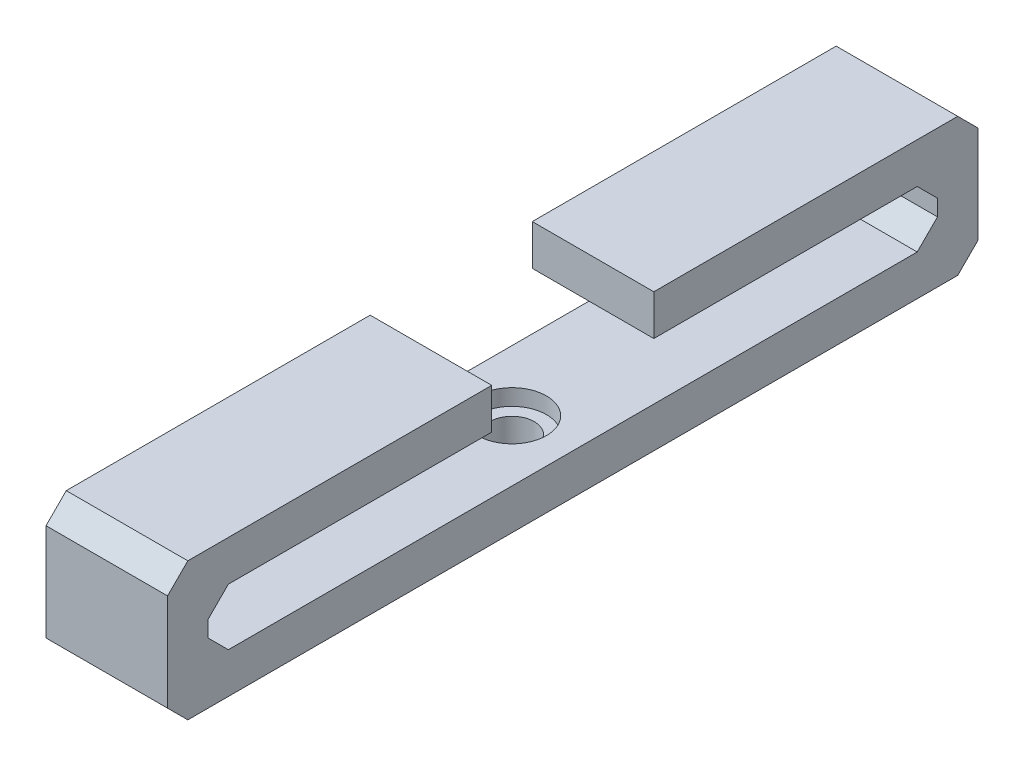
SolidWorks part; units mm, degrees
ref_plane "Front Plane" through (0, 0, 0) normal (0, 0, 1) x (1, 0, 0)
ref_plane "Top Plane" through (0, 0, 0) normal (0, 1, 0) x (1, 0, 0)
ref_plane "Right Plane" through (0, 0, 0) normal (1, 0, 0) x (0, 0, -1)
sketch "Sketch1" plane through (0, 0, 0) normal (1, 0, 0) x (0, 0, -1)
  line L0 (10, 17) -> (10, 12)
  line L1 (10, 12) -> (45, 12)
  line L2 (45, 12) -> (45, 5)
  line L3 (45, 5) -> (-45, 5)
  line L5 (-50, 0) -> (50, 0)
  line L6 (50, 0) -> (50, 17)
  line L7 (50, 17) -> (10, 17)
  line L8 (0, 5) -> (0, 0) construction
  line L9 (-45, 12) -> (-45, 5)
  line L10 (-10, 17) -> (-10, 12)
  line L11 (-50, 17) -> (-10, 17)
  line L12 (-10, 12) -> (-45, 12)
  line L13 (-50, 0) -> (-50, 17)
  point P6 (0, -2.8354)
  point P11 (0, 0)
  point P12 (50, 11.1646)
  point P13 (0, 4.3625)
  dimension "D1" = 7
  dimension "D2" = 50
  dimension "D3" = 5
  dimension "D4" = 5
  dimension "D5" = 10
  dimension "D6" = 5
extrude "Boss-Extrude1" add sketch "Sketch1" along normal mid plane 15
chamfer "Chamfer1" distance 2.5 angle 45 8 edges at (0, 12, -45) (0, 17, -50) (0, 12, 45) (0, 17, 50) (0, 0, -50) (0, 5, -45) (0, 0, 50) (0, 5, 45)
sketch "Sketch2" plane through (0, 5, 0) normal (0, 1, 0) x (1, 0, 0)
  circle A0 centre (0, 0) radius 2.75
  dimension "D1" = 5.5
extrude "Cut-Extrude1" cut sketch "Sketch2" against normal through all
sketch "Sketch3" plane through (0, 5, 0) normal (0, 1, 0) x (1, 0, 0)
  circle A0 centre (0, 0) radius 4.25
  dimension "D1" = 8.5
extrude "Cut-Extrude2" cut sketch "Sketch3" against normal blind 2
